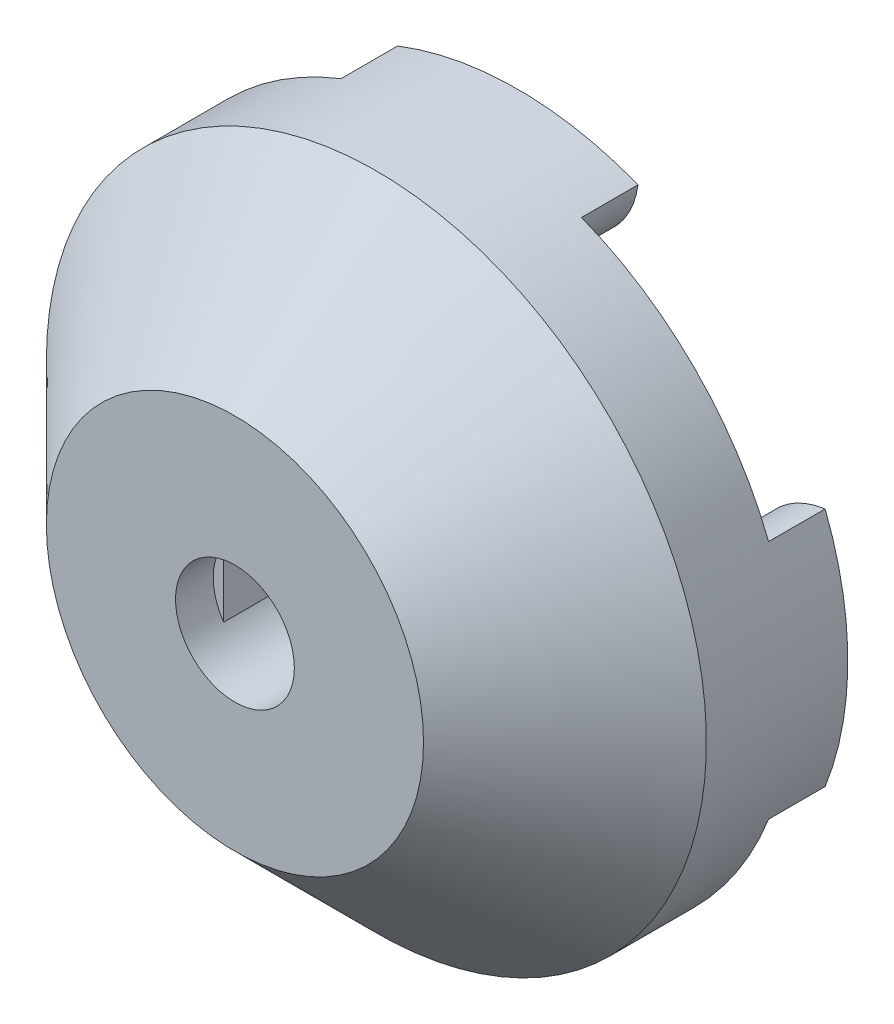
SolidWorks part; units mm, degrees
ref_plane "Front Plane" through (0, 0, 0) normal (0, 0, 1) x (1, 0, 0)
ref_plane "Top Plane" through (0, 0, 0) normal (0, 1, 0) x (1, 0, 0)
ref_plane "Right Plane" through (0, 0, 0) normal (1, 0, 0) x (0, 0, -1)
sketch "BaseModelSketch" plane through (0, 0, 0) normal (0, 0, 1) x (1, 0, 0)
  circle A0 centre (0, 0) radius 17.5
  dimension "D1" = 35
extrude "BaseModel" add sketch "BaseModelSketch" against normal blind 12
sketch "KeyToothSketch" plane through (0, 0, -12) normal (0, 0, -1) x (-1, 0, 0)
  line L0 (0, 17.5) -> (0, -17.5) construction
  circle A0 centre (0, 0) radius 12.5 construction
  circle A1 centre (0, 0) radius 17.5 construction
  arc A2 (6.375, -16.2975) -> (1.4077, -12.4205) centre (1.9144, -16.8919) ccw
  arc A3 (-1.4077, -12.4205) -> (-6.375, -16.2975) centre (-1.9144, -16.8919) ccw
  arc A4 (1.4077, -12.4205) -> (-1.4077, -12.4205) centre (0, 0) cw
  arc A5 (-6.375, -16.2975) -> (6.375, -16.2975) centre (0, 0) ccw
  dimension "D1" = 25
  dimension "D2" = 4.5
  dimension "D3" = 4.5
  dimension "D4" = 17.5
  dimension "D5" = 12.75
extrude "KeyTooth" add sketch "KeyToothSketch" along normal blind 3
pattern_circular "PatternKey" count 4 over 360 about axis through (0, 0, 0) along (0, 0, 1) of "KeyTooth"
sketch "CenterHoleSupportExtrusionSketch" plane through (0, 0, -12) normal (0, 0, -1) x (-1, 0, 0)
  circle A0 centre (0, 0) radius 6
  dimension "D1" = 12
extrude "CenterHoleSupportExtrusion" add sketch "CenterHoleSupportExtrusionSketch" along normal blind 3
sketch "InnerHoleWithKeySketch" plane through (0, 0, 0) normal (0, 0, 1) x (1, 0, 0)
  line L0 (-2.6, 1.7783) -> (-2.6, -1.7783)
  arc A0 (-2.6, -1.7783) -> (-2.6, 1.7783) centre (0, 0) ccw
  dimension "D1" = 6.3
  dimension "D2" = 2.6
extrude "InnerHoleWithKey" cut sketch "InnerHoleWithKeySketch" against normal through all
sketch "HoleforSpringAxleSketch" plane through (0, 0, -15) normal (0, 0, -1) x (-1, 0, 0)
  circle A0 centre (0, 0) radius 3.5
  dimension "D1" = 7
extrude "HoleforSpringAxle" cut sketch "HoleforSpringAxleSketch" against normal blind 3.5
sketch "EncoderKeyEnd" plane through (0, 0, 0) normal (0, 0, 1) x (1, 0, 0)
  circle A0 centre (0, 0) radius 3.15
extrude "EndoerKeyEnd" cut sketch "EncoderKeyEnd" against normal blind 2
chamfer "Chamfer1" distance 7.5 angle 45 1 edges at (17.5, 0, 0)
